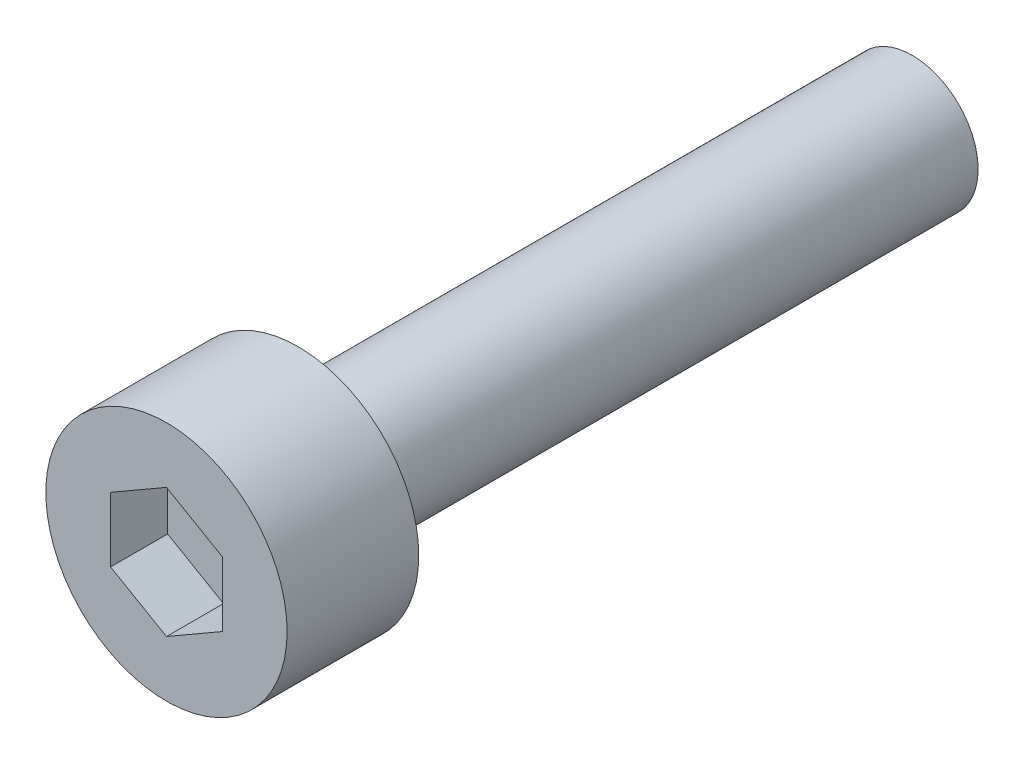
SolidWorks part; units mm, degrees
material "AISI 304"
ref_plane "Front Plane" through (0, 0, 0) normal (0, 0, 1) x (1, 0, 0)
ref_plane "Top Plane" through (0, 0, 0) normal (0, 1, 0) x (1, 0, 0)
ref_plane "Right Plane" through (0, 0, 0) normal (1, 0, 0) x (0, 0, -1)
sketch "草图1" plane through (0, 0, 0) normal (0, 0, 1) x (1, 0, 0)
  circle A0 centre (0, 0) radius 2.75
  dimension "D1" = 5.5
extrude "凸台-拉伸1" add sketch "草图1" along normal blind 3
sketch "草图2" plane through (0, 0, 3) normal (0, 0, 1) x (1, 0, 0)
  line L1 (1.275, -0.7361) -> (1.275, 0.7361)
  line L2 (1.275, 0.7361) -> (0, 1.4722)
  line L3 (0, 1.4722) -> (-1.275, 0.7361)
  line L4 (-1.275, 0.7361) -> (-1.275, -0.7361)
  line L5 (-1.275, -0.7361) -> (0, -1.4722)
  line L6 (0, -1.4722) -> (1.275, -0.7361)
  circle A0 centre (0, 0) radius 1.275 construction
  dimension "D1" = 2.55
extrude "切除-拉伸1" cut sketch "草图2" against normal blind 1.3
sketch "草图3" plane through (0, 0, 0) normal (0, 0, -1) x (-1, 0, 0)
  circle A0 centre (0, 0) radius 1.5
  dimension "D1" = 3
extrude "凸台-拉伸2" add sketch "草图3" along normal blind 14
cosmetic thread "装饰螺纹线1" parameters "D2"=3
